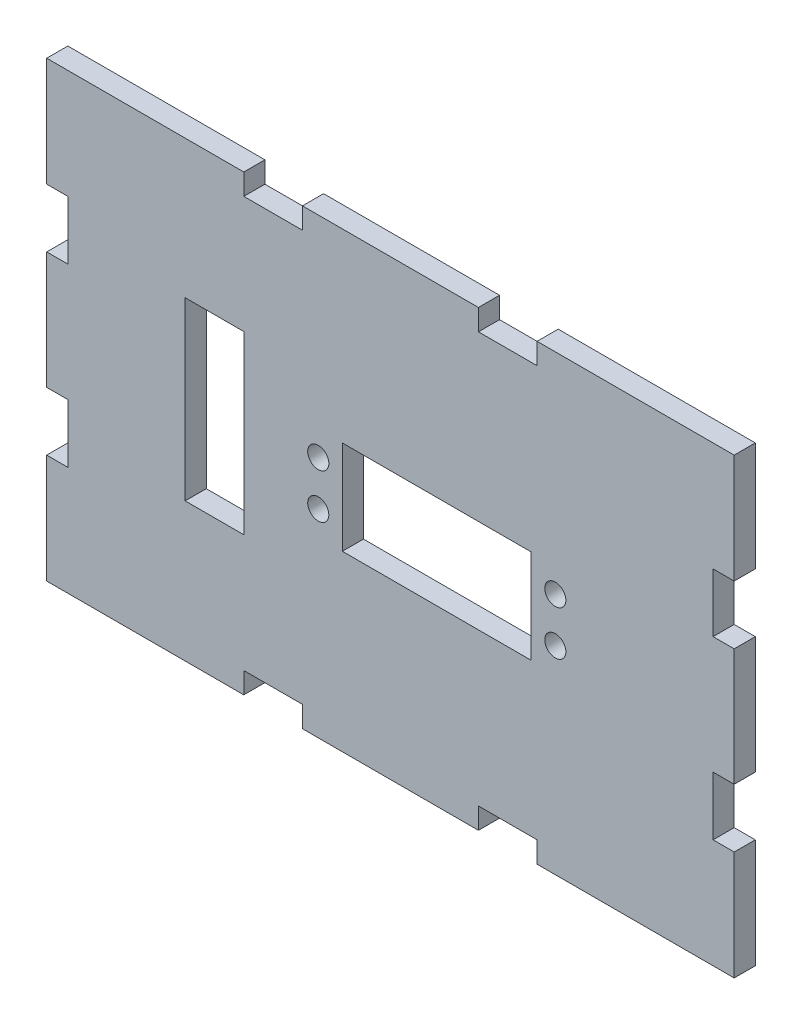
SolidWorks part; units mm, degrees
ref_plane "Front Plane" through (0, 0, 0) normal (0, 0, 1) x (1, 0, 0)
ref_plane "Top Plane" through (0, 0, 0) normal (0, 1, 0) x (1, 0, 0)
ref_plane "Right Plane" through (0, 0, 0) normal (1, 0, 0) x (0, 0, -1)
sketch "Sketch2" plane through (0, 0, 0) normal (0, 0, 1) x (1, 0, 0)
  line L1 (0, 0) -> (148.844, 0)
  line L2 (0, 0) -> (0, 98.044)
  line L3 (0, 98.044) -> (148.844, 98.044)
  line L4 (148.844, 0) -> (148.844, 98.044)
  dimension "D1" = 148.844
  dimension "D2" = 98.044
extrude "Boss-Extrude1" add sketch "Sketch2" along normal blind 4.572
sketch "Sketch3" plane through (0, 0, 4.572) normal (0, 0, 1) x (1, 0, 0)
  line L0 (0, 0) -> (148.844, 0) construction
  line L1 (42.672, 0) -> (55.372, 0)
  line L2 (42.672, 0) -> (42.672, 4.572)
  line L3 (42.672, 4.572) -> (55.372, 4.572)
  line L4 (55.372, 0) -> (55.372, 4.572)
  line L5 (0, 98.044) -> (0, 0) construction
  line L6 (93.472, 0) -> (106.172, 0)
  line L7 (93.472, 0) -> (93.472, 4.572)
  line L8 (93.472, 4.572) -> (106.172, 4.572)
  line L9 (106.172, 0) -> (106.172, 4.572)
  line L10 (0, 23.622) -> (4.572, 23.622)
  line L11 (0, 23.622) -> (0, 36.322)
  line L12 (0, 36.322) -> (4.572, 36.322)
  line L13 (4.572, 23.622) -> (4.572, 36.322)
  line L14 (148.844, 98.044) -> (0, 98.044) construction
  line L15 (0, 74.422) -> (4.572, 74.422)
  line L16 (0, 74.422) -> (0, 61.722)
  line L17 (0, 61.722) -> (4.572, 61.722)
  line L18 (4.572, 74.422) -> (4.572, 61.722)
  line L19 (42.672, 98.044) -> (55.372, 98.044)
  line L20 (42.672, 98.044) -> (42.672, 93.472)
  line L21 (42.672, 93.472) -> (55.372, 93.472)
  line L22 (55.372, 98.044) -> (55.372, 93.472)
  line L23 (148.844, 0) -> (148.844, 98.044) construction
  line L24 (93.472, 98.044) -> (106.172, 98.044)
  line L25 (93.472, 98.044) -> (93.472, 93.472)
  line L26 (93.472, 93.472) -> (106.172, 93.472)
  line L27 (106.172, 98.044) -> (106.172, 93.472)
  line L28 (148.844, 74.422) -> (144.272, 74.422)
  line L29 (148.844, 74.422) -> (148.844, 61.722)
  line L30 (148.844, 61.722) -> (144.272, 61.722)
  line L31 (144.272, 74.422) -> (144.272, 61.722)
  line L33 (148.844, 36.322) -> (144.272, 36.322)
  line L34 (148.844, 36.322) -> (148.844, 23.622)
  line L35 (148.844, 23.622) -> (144.272, 23.622)
  line L36 (144.272, 36.322) -> (144.272, 23.622)
  dimension "D1" = 4.572
  dimension "D2" = 4.572
  dimension "D3" = 4.572
  dimension "D4" = 4.572
  dimension "D5" = 4.572
  dimension "D6" = 4.572
  dimension "D7" = 4.572
  dimension "D8" = 4.572
  dimension "D9" = 12.7
  dimension "D10" = 12.7
  dimension "D11" = 38.1
  dimension "D12" = 42.672
  dimension "D13" = 12.7
  dimension "D14" = 12.7
  dimension "D15" = 38.1
  dimension "D16" = 42.672
  dimension "D17" = 12.7
  dimension "D18" = 12.7
  dimension "D19" = 12.7
  dimension "D20" = 12.7
  dimension "D21" = 25.4
  dimension "D22" = 25.4
  dimension "D23" = 23.622
  dimension "D24" = 23.622
extrude "Cut-Extrude1" cut sketch "Sketch3" against normal blind 4.572
sketch "Sketch4" plane through (0, 0, 4.572) normal (0, 0, 1) x (1, 0, 0)
  line L0 (64.008, 47.752) -> (104.902, 47.752) construction
  line L1 (64.008, 57.912) -> (104.902, 57.912)
  line L2 (64.008, 57.912) -> (64.008, 37.592)
  line L3 (64.008, 37.592) -> (104.902, 37.592)
  line L4 (104.902, 57.912) -> (104.902, 37.592)
  line L5 (55.372, 4.572) -> (42.672, 4.572) construction
  line L6 (0, 23.622) -> (0, 0) construction
  line L7 (84.455, 57.912) -> (84.455, 37.592) construction
  circle A0 centre (58.794, 52.578) radius 2.286
  circle A4 centre (110.116, 52.578) radius 2.286
  circle A5 centre (110.116, 42.926) radius 2.286
  circle A6 centre (58.794, 42.926) radius 2.286
  dimension "D5" = 4.572
  dimension "D1" = 40.894
  dimension "D2" = 20.32
  dimension "D3" = 33.02
  dimension "D4" = 64.008
  dimension "D7" = 5.214
  dimension "D6" = 4.826
extrude "Cut-Extrude2" cut sketch "Sketch4" against normal through all
sketch "Sketch5" plane through (0, 0, 4.572) normal (0, 0, 1) x (1, 0, 0)
  line L0 (42.672, 93.472) -> (55.372, 93.472) construction
  line L1 (29.972, 68.1265) -> (42.672, 68.1265)
  line L2 (29.972, 68.1265) -> (29.972, 30.0265)
  line L3 (29.972, 30.0265) -> (42.672, 30.0265)
  line L4 (42.672, 68.1265) -> (42.672, 30.0265)
  line L6 (4.572, 61.722) -> (4.572, 74.422) construction
  dimension "D1" = 12.7
  dimension "D2" = 38.1
  dimension "D3" = 25.3455
  dimension "D4" = 38.1
extrude "Cut-Extrude3" cut sketch "Sketch5" against normal blind 4.572
equation "\"D7@Sketch4\"=0.29527559-0.09"
